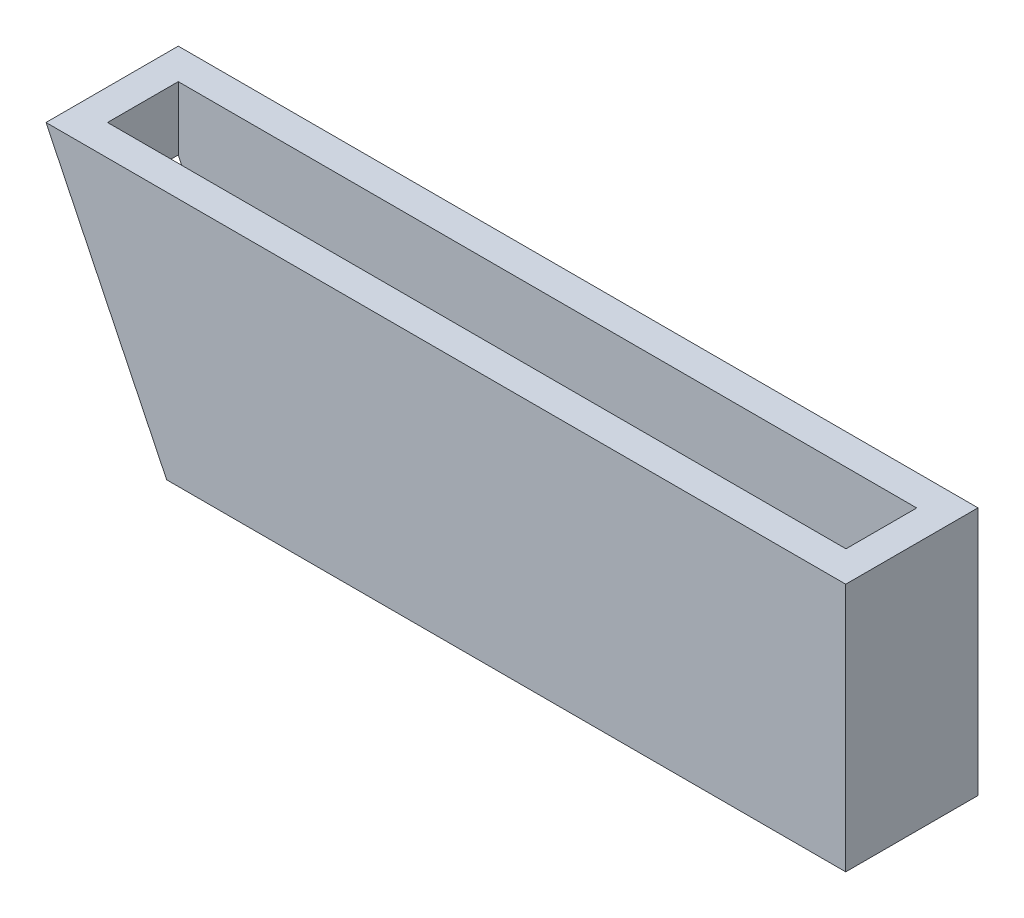
SolidWorks part; units mm, degrees
ref_plane "Plan de face" through (0, 0, 0) normal (0, 0, 1) x (1, 0, 0)
ref_plane "Plan de dessus" through (0, 0, 0) normal (0, 1, 0) x (1, 0, 0)
ref_plane "Plan de droite" through (0, 0, 0) normal (1, 0, 0) x (0, 0, -1)
sketch "Esquisse5" plane through (0, 0, 0) normal (0, 1, 0) x (1, 0, 0)
  line L1 (0, 0) -> (260, 0)
  line L2 (0, 0) -> (0, -10)
  line L3 (0, -10) -> (260, -10)
  line L4 (260, 0) -> (260, -10)
  line L5 (0, 0) -> (10, 0)
  line L6 (0, 0) -> (0, 23)
  line L7 (0, 23) -> (10, 23)
  line L8 (10, 0) -> (10, 23)
  line L9 (260, 0) -> (250.0762, 0)
  line L10 (260, 0) -> (260, 23)
  line L11 (260, 23) -> (250.0762, 23)
  line L12 (250.0762, 0) -> (250.0762, 23)
  line L13 (0, 23) -> (260, 23)
  line L14 (0, 23) -> (0, 32.9986)
  line L15 (0, 32.9986) -> (260, 32.9986)
  line L16 (260, 23) -> (260, 32.9986)
extrude "Boss.-Extru.4" add sketch "Esquisse5" along normal blind 81 contours L11 L16 L15 L14 L7 L13 | L1 L8 L7 L6 | L4 L1 L2 L3 | L12 L1 L10 L11
ref_plane "Plan3" through (0, 81, 10) normal (0, -1, 0) x (-1, 0, 0)
sketch "Esquisse7" plane through (0, 0, -32.9986) normal (0, 0, -1) x (-1, 0, 0)
  line L0 (0, 81) -> (-39.2301, 0)
  line L1 (0, 0) -> (-260, 0) construction
  line L2 (-260, 81) -> (-220.7699, 0)
  line L7 (-260, 81) -> (-220.7699, 0)
  line L9 (-39.2301, 0) -> (0, 81)
  line L11 (0, 81) -> (-39.2301, 0)
  line L12 (-260, 81) -> (-220.7699, 0)
extrude "Enlèv. mat.-Extru.2" cut sketch "Esquisse7" along normal blind 2 and the other way blind 227 contours L2 L0 L1
sketch "Esquisse9" plane through (0, 0, -32.9986) normal (0, 0, -1) x (-1, 0, 0)
  line L0 (-260, 81) -> (-220.7699, 0)
  line L1 (-39.2301, 0) -> (-260, 0) construction
